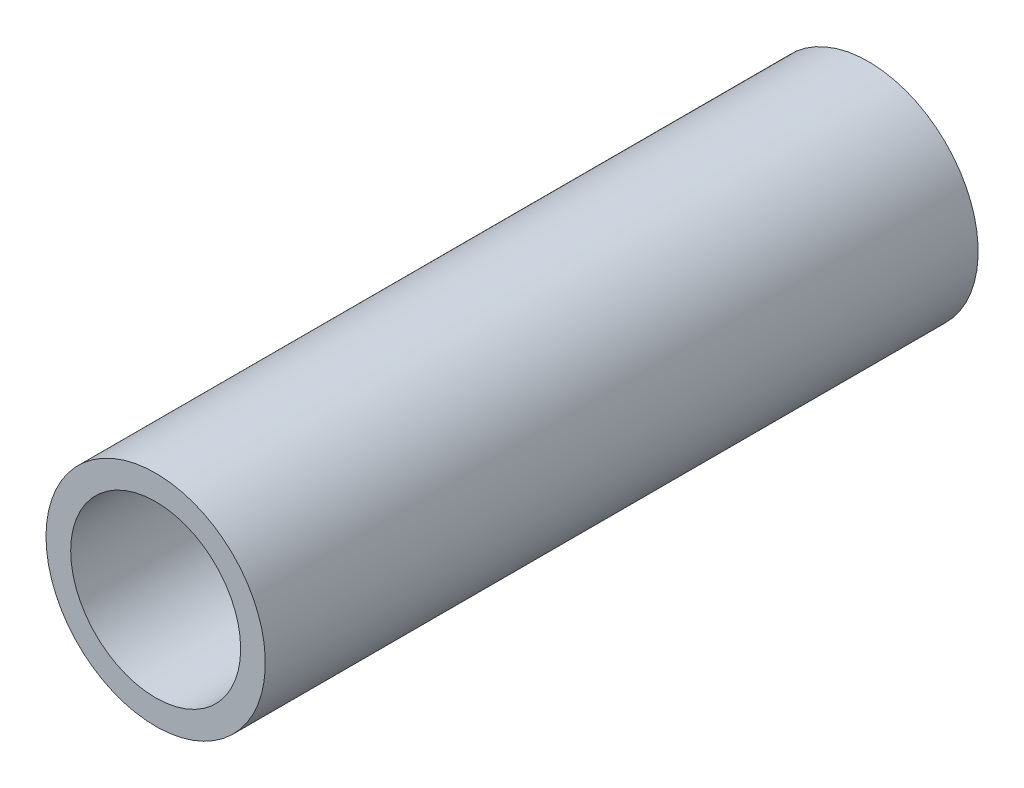
SolidWorks part; units mm, degrees
ref_plane "Спереди" through (0, 0, 0) normal (0, 0, 1) x (1, 0, 0)
ref_plane "Сверху" through (0, 0, 0) normal (0, 1, 0) x (1, 0, 0)
ref_plane "Справа" through (0, 0, 0) normal (1, 0, 0) x (0, 0, -1)
sketch "Эскиз1" plane through (0, 0, 0) normal (0, 0, 1) x (1, 0, 0)
  circle A0 centre (0, 0) radius 1
  circle A1 centre (0, 0) radius 0.775
extrude "Бобышка-Вытянуть1" add sketch "Эскиз1" along normal blind 6.5
